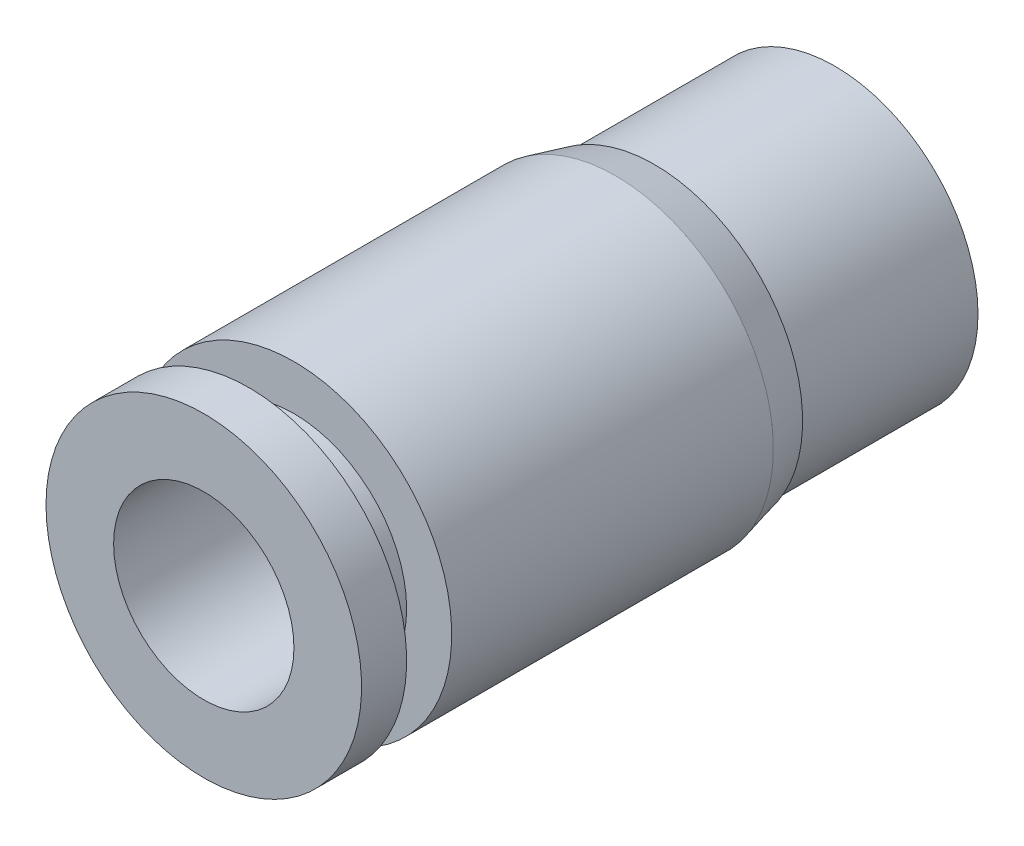
SolidWorks part; units mm, degrees
ref_plane "Front Plane" through (0, 0, 0) normal (0, 0, 1) x (1, 0, 0)
ref_plane "Top Plane" through (0, 0, 0) normal (0, 1, 0) x (1, 0, 0)
ref_plane "Right Plane" through (0, 0, 0) normal (1, 0, 0) x (0, 0, -1)
ref_axis "Axis1" through (0, 0, -4.7) along (0, 0, 1)
sketch "Sketch2" plane through (0, 0, 0) normal (1, 0, 0) x (0, 0, -1)
  line L0 (-2, 2) -> (-10, 2)
  line L1 (-10, 2) -> (-10, 3.5)
  line L2 (-10, 3.5) -> (-9, 3.5)
  line L3 (-9, 3.5) -> (-9, 2.5)
  line L4 (-9, 2.5) -> (-8, 2.5)
  line L5 (-8, 2.5) -> (-8, 3.5)
  line L6 (-8, 3.5) -> (-0.8642, 3.5)
  line L8 (-0.8642, 3.5) -> (0, 3.2839)
  line L9 (0, 3.175) -> (4, 3.175)
  line L10 (-2, 2) -> (-2, 1.8547)
  line L11 (-2, 1.8547) -> (4, 1.8547)
  line L12 (4, 1.8547) -> (4, 3.175)
  line L13 (0, 3.2839) -> (0, 3.175)
revolve "Revolve1" add sketch "Sketch2" angle 360 about axis through (0, 0, -4.7) along (0, 0, 1)
